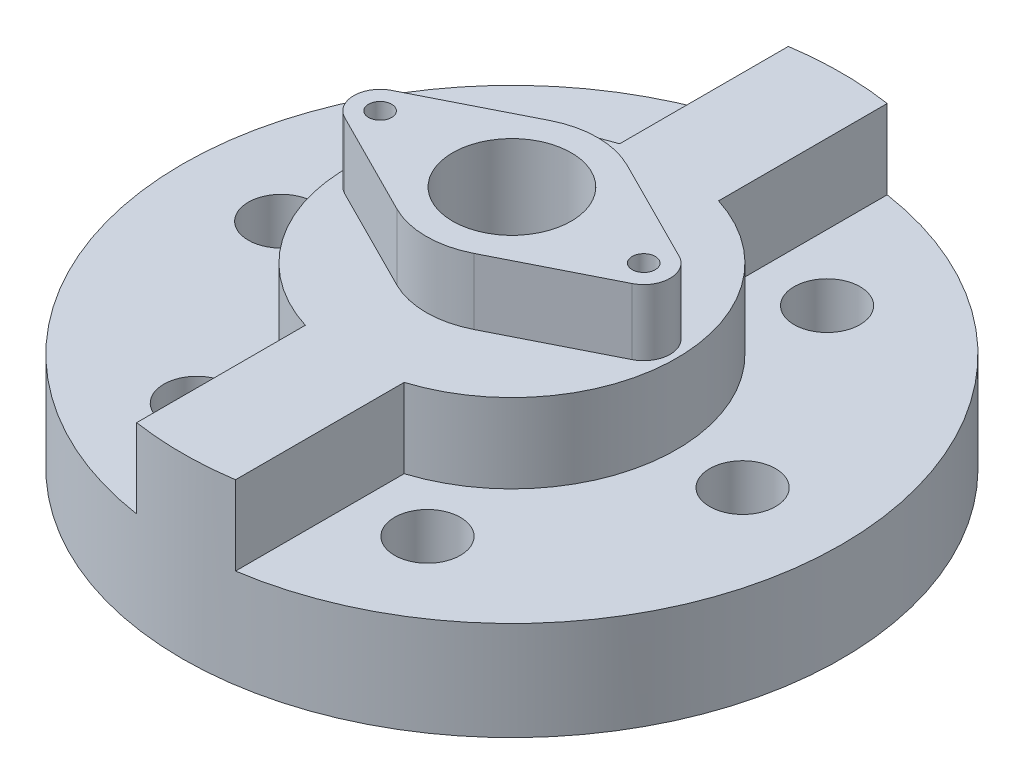
SolidWorks part; units mm, degrees
ref_plane "Front Plane" through (0, 0, 0) normal (0, 0, 1) x (1, 0, 0)
ref_plane "Top Plane" through (0, 0, 0) normal (0, 1, 0) x (1, 0, 0)
ref_plane "Right Plane" through (0, 0, 0) normal (1, 0, 0) x (0, 0, -1)
sketch "Sketch1" plane through (0, 0, 0) normal (0, 1, 0) x (1, 0, 0)
  circle A0 centre (0, 0) radius 50
  dimension "D1" = 100
extrude "Boss-Extrude1" add sketch "Sketch1" along normal blind 15
sketch "Sketch2" plane through (0, 15, 0) normal (0, 1, 0) x (1, 0, 0)
  line L0 (0, 0) -> (0, 56.5456) construction
  line L1 (7.5, 49.4343) -> (7.5, 23.8485)
  line L2 (-7.5, 49.4343) -> (-7.5, 23.8485)
  line L3 (-7.5, -23.8485) -> (-7.5, -49.4343)
  line L4 (7.5, -23.8485) -> (7.5, -49.4343)
  circle A0 centre (0, 0) radius 50 construction
  arc A1 (7.5, 49.4343) -> (-7.5, 49.4343) centre (0, 0) ccw
  arc A2 (7.5, -23.8485) -> (7.5, 23.8485) centre (0, 0) ccw
  arc A3 (-7.5, -49.4343) -> (7.5, -49.4343) centre (0, 0) ccw
  arc A4 (-7.5, 23.8485) -> (-7.5, -23.8485) centre (0, 0) ccw
  dimension "D1" = 50
  dimension "D2" = 15
extrude "Boss-Extrude2" add sketch "Sketch2" along normal blind 12
sketch "Sketch3" plane through (0, 27, 0) normal (0, 1, 0) x (1, 0, 0)
  line L0 (73.6316, 0) -> (-61.7187, 0) construction
  line L1 (0, 0) -> (0, 40.3348) construction
  line L2 (-21.8, 3.5721) -> (-5.85, 11.6094)
  line L3 (-21.8, -3.5721) -> (-5.85, -11.6094)
  line L4 (21.8, -3.5721) -> (5.85, -11.6094)
  line L5 (21.8, 3.5721) -> (5.85, 11.6094)
  arc A0 (-5.85, -11.6094) -> (5.85, -11.6094) centre (0, 0) ccw
  arc A1 (-21.8, 3.5721) -> (-21.8, -3.5721) centre (-20, 0) ccw
  arc A2 (21.8, 3.5721) -> (21.8, -3.5721) centre (20, 0) cw
  arc A3 (5.85, 11.6094) -> (-5.85, 11.6094) centre (0, 0) ccw
  circle A4 centre (-20, 0) radius 1.75
  circle A5 centre (20, 0) radius 1.75
  point P17 (73.6316, 0)
  dimension "D1" = 26
  dimension "D2" = 8
  dimension "D4" = 3.5
  dimension "D3" = 20
extrude "Boss-Extrude3" add sketch "Sketch3" along normal blind 10
hole_wizard "Hole1" positions "Sketch4" profile "Sketch5" legacy end condition through all
sketch "Sketch4" plane through (0, 37, 0) normal (0, 1, 0) x (1, 0, 0)
  point P0 (0, 0)
sketch "Sketch5" plane through (0, 37, 0) normal (1, 0, 0) x (0, 0, 1)
  line L0 (0, 0) -> (0, 37)
  line L1 (0, 37) -> (9, 37)
  line L2 (9, 37) -> (9, 0)
  line L3 (9, 0) -> (0, 0)
  line L4 (0, 110) -> (0, -10) construction
  dimension "Diameter" = 18
  dimension "Depth" = 37
hole_wizard "Hole2" positions "Sketch6" profile "Sketch7" legacy end condition through all
sketch "Sketch6" plane through (0, 15, 0) normal (0, 1, 0) x (1, 0, 0)
  point P0 (35, 0)
  dimension "D1" = 35
sketch "Sketch7" plane through (35, 15, 0) normal (1, 0, 0) x (0, 0, 1)
  line L0 (0, 0) -> (0, 15)
  line L1 (0, 15) -> (5, 15)
  line L2 (5, 15) -> (5, 0)
  line L3 (5, 0) -> (0, 0)
  line L4 (0, 110) -> (0, -10) construction
  dimension "Diameter" = 10
  dimension "Depth" = 15
pattern_circular "CirPattern1" count 6 over 360 about axis through (0, 0, 0) along (0, 1, 0) of "Hole2"
